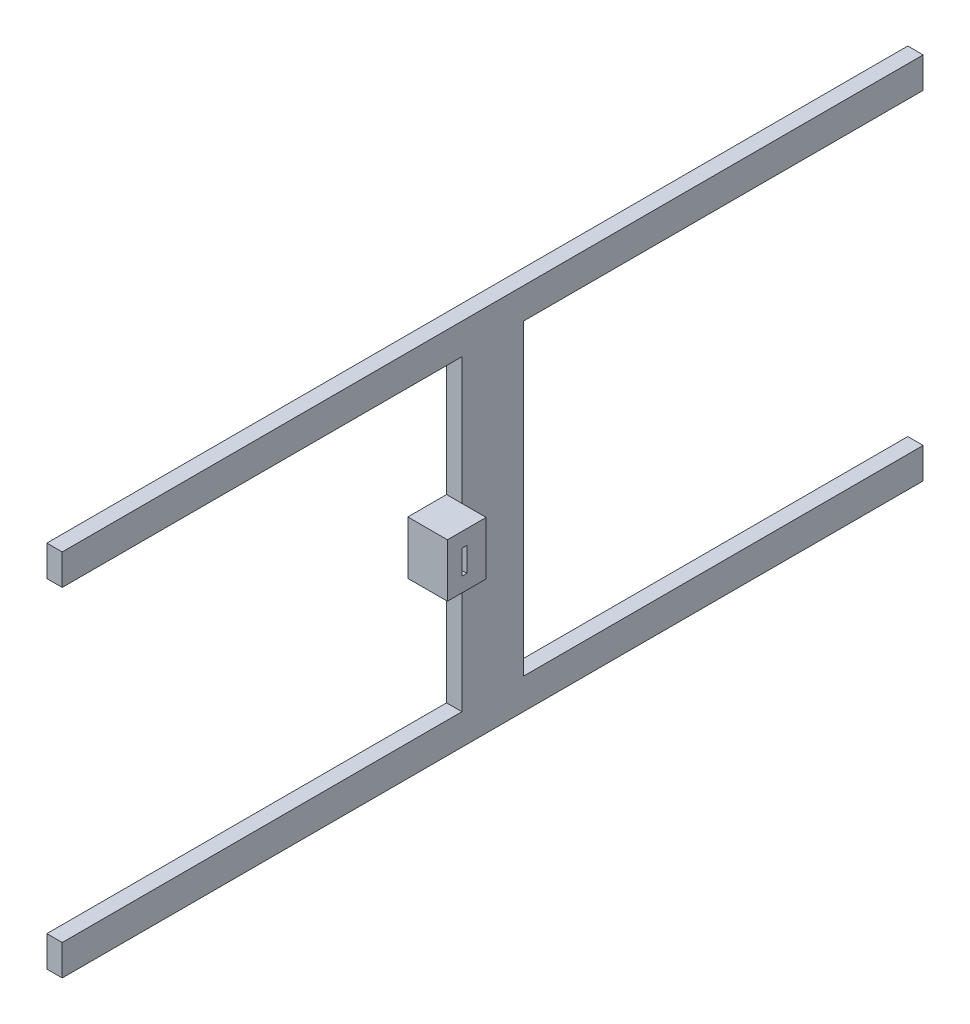
SolidWorks part; units mm, degrees
ref_plane "Front" through (0, 0, 0) normal (0, 0, 1) x (1, 0, 0)
ref_plane "Top" through (0, 0, 0) normal (0, 1, 0) x (1, 0, 0)
ref_plane "Right" through (0, 0, 0) normal (1, 0, 0) x (0, 0, -1)
sketch "Sketch1" plane through (0, 0, 0) normal (1, 0, 0) x (0, 0, -1)
  line L0 (0, 0) -> (32.4322, 0)
  line L1 (32.4322, 31.75) -> (32.4322, -31.75)
  line L2 (32.4322, -31.75) -> (114.9822, -31.75)
  line L3 (114.9822, -31.75) -> (114.9822, -38.1)
  line L4 (114.9822, -38.1) -> (-62.8178, -38.1)
  line L5 (-62.8178, -38.1) -> (-62.8178, -31.75)
  line L6 (-62.8178, -31.75) -> (19.7322, -31.75)
  line L7 (19.7322, -31.75) -> (19.7322, 31.75)
  line L8 (19.7322, 0) -> (0, 0)
  line L9 (-62.8178, 31.75) -> (19.7322, 31.75)
  line L10 (-62.8178, 38.1) -> (-62.8178, 31.75)
  line L11 (114.9822, 38.1) -> (-62.8178, 38.1)
  line L12 (114.9822, 31.75) -> (114.9822, 38.1)
  line L13 (32.4322, 31.75) -> (114.9822, 31.75)
  point P10 (-62.8178, -34.925)
  dimension "D1" = 177.8
  dimension "D2" = 12.7
  dimension "D3" = 82.55
  dimension "D4" = 31.75
  dimension "D5" = 6.35
extrude "Boss-Extrude1" add sketch "Sketch1" along normal blind 3.175 contours L1 L13 L12 L11 L10 L9 L7 L0 | L7 L6 L5 L4 L3 L2 L1 L0
sketch "Sketch2" plane through (0, 0, 0) normal (-1, 0, 0) x (0, 0, 1)
  line L0 (-19.7322, 2.5) -> (-14.7322, 2.5)
  line L1 (-19.7322, -31.75) -> (-19.7322, 31.75) construction
  line L2 (-14.7322, 2.5) -> (-14.7322, -2.5)
  line L3 (-14.7322, -2.5) -> (-19.7322, -2.5)
  line L4 (-19.7322, -31.75) -> (-19.7322, -2.5)
  line L5 (-19.7322, 2.5) -> (-19.7322, 5.5)
  line L6 (-19.7322, 5.5) -> (-11.7322, 5.5)
  line L7 (-11.7322, 5.5) -> (-11.7322, -5.5)
  line L8 (-11.7322, -5.5) -> (-19.7322, -5.5)
  line L16 (-32.4322, 31.75) -> (-32.4322, -31.75)
  line L17 (-32.4322, -31.75) -> (-114.9822, -31.75)
  line L18 (-114.9822, -31.75) -> (-114.9822, -38.1)
  line L19 (-114.9822, -38.1) -> (62.8178, -38.1)
  line L20 (62.8178, -38.1) -> (62.8178, -31.75)
  line L21 (62.8178, -31.75) -> (-19.7322, -31.75)
  line L22 (-19.7322, -31.75) -> (-19.7322, 31.75)
  line L23 (-19.7322, 31.75) -> (62.8178, 31.75)
  line L24 (62.8178, 31.75) -> (62.8178, 38.1)
  line L25 (62.8178, 38.1) -> (-114.9822, 38.1)
  line L26 (-114.9822, 38.1) -> (-114.9822, 31.75)
  line L27 (-114.9822, 31.75) -> (-32.4322, 31.75)
  line L28 (-32.4322, 31.75) -> (-32.4322, -31.75)
  line L29 (-32.4322, -31.75) -> (-114.9822, -31.75)
  line L30 (-114.9822, -31.75) -> (-114.9822, -38.1)
  line L31 (-114.9822, -38.1) -> (62.8178, -38.1)
  line L32 (62.8178, -38.1) -> (62.8178, -31.75)
  line L33 (62.8178, -31.75) -> (-19.7322, -31.75)
  line L34 (-19.7322, 2.5) -> (-19.7322, 31.75)
  line L35 (-19.7322, 31.75) -> (62.8178, 31.75)
  line L36 (62.8178, 31.75) -> (62.8178, 38.1)
  line L37 (62.8178, 38.1) -> (-114.9822, 38.1)
  line L38 (-114.9822, 38.1) -> (-114.9822, 31.75)
  line L39 (-114.9822, 31.75) -> (-32.4322, 31.75)
  point P16 (-14.7322, 0)
  point P18 (-19.7322, 0)
  line M25 (-19.7322, -31.75) -> (-19.7322, 31.75)
  dimension "D2" = 5
  dimension "D3" = 5
  dimension "D4" = 3
  dimension "D5" = 3
  dimension "D6" = 0
  dimension "D7" = 3
  dimension "D1" = 0
extrude "Boss-Extrude2" add sketch "Sketch2" against normal blind 5 contours L8 L7 L6 L0 L2 L3 L4 M25
sketch "Sketch4" plane through (5, 0, 0) normal (1, 0, 0) x (0, 0, -1)
  line L0 (19.7322, 5.5) -> (11.7322, 5.5)
  line L1 (11.7322, 5.5) -> (11.7322, -5.5)
  line L2 (11.7322, -5.5) -> (19.7322, -5.5)
  line L3 (19.7322, -5.5) -> (19.7322, -2.5)
  line L4 (19.7322, -2.5) -> (15.7322, -2.5)
  line L5 (14.7322, -2.5) -> (19.7322, -2.5) construction
  line L6 (15.7322, -2.5) -> (15.7322, 2.5)
  line L7 (19.7322, 2.5) -> (14.7322, 2.5) construction
  line L8 (15.7322, 2.5) -> (19.7322, 2.5)
  line L9 (19.7322, 2.5) -> (19.7322, 5.5)
  line L10 (19.7322, 2.5) -> (19.7322, -2.5)
  line L11 (15.7322, 2.5) -> (14.7322, 2.5)
  line L12 (14.7322, 2.5) -> (14.7322, -2.5)
  line L13 (14.7322, -2.5) -> (15.7322, -2.5)
  line M1 (11.7322, -5.5) -> (19.7322, -5.5)
  line M2 (19.7322, -5.5) -> (19.7322, -2.5)
  line M3 (19.7322, -2.5) -> (14.7322, -2.5)
  line M4 (14.7322, -2.5) -> (14.7322, 2.5)
  line M5 (14.7322, 2.5) -> (19.7322, 2.5)
  line M6 (19.7322, 2.5) -> (19.7322, 5.5)
  line M7 (19.7322, 5.5) -> (11.7322, 5.5)
  line M8 (11.7322, 5.5) -> (11.7322, -5.5)
  dimension "D1" = 1
extrude "Boss-Extrude3" add sketch "Sketch4" along normal blind 3.175 contours M8 M1 M2 M3 M4 M5 M6 M7 | L10 L6 M5 M3
